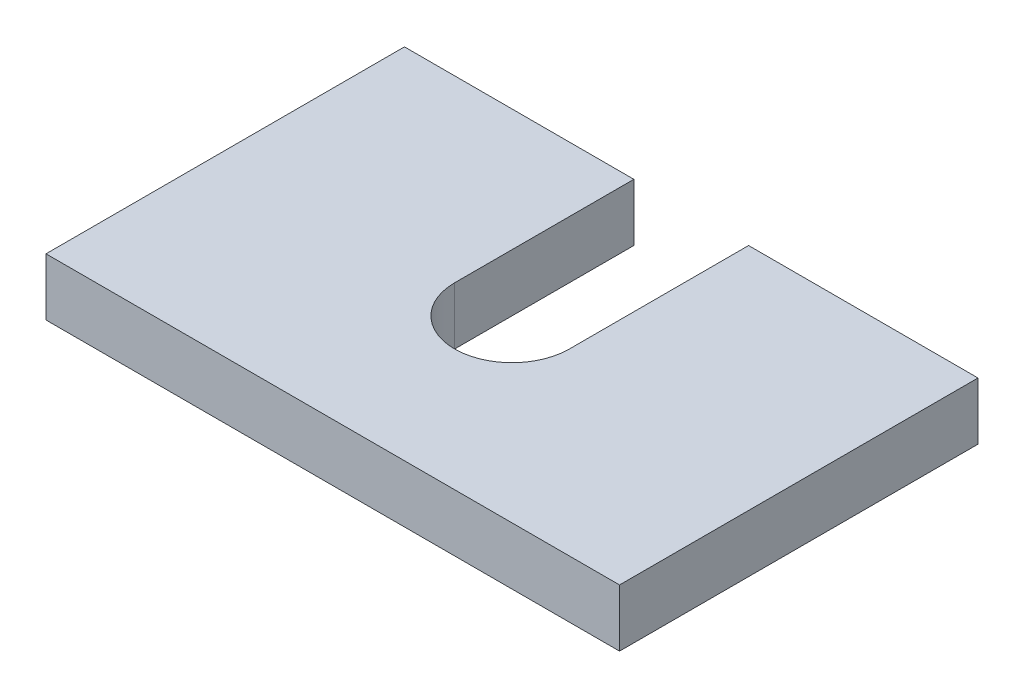
SolidWorks part; units mm, degrees
material "AISI 4340 Steel, normalized"
ref_plane "Front Plane" through (0, 0, 0) normal (0, 0, 1) x (1, 0, 0)
ref_plane "Top Plane" through (0, 0, 0) normal (0, 1, 0) x (1, 0, 0)
ref_plane "Right Plane" through (0, 0, 0) normal (1, 0, 0) x (0, 0, -1)
sketch "Sketch1" plane through (0, 0, 0) normal (0, 1, 0) x (1, 0, 0)
  line L0 (-4, 0) -> (-4, 12.5)
  line L1 (-20, -12.5) -> (20, -12.5)
  line L2 (-20, -12.5) -> (-20, 12.5)
  line L3 (-20, 12.5) -> (-4, 12.5)
  line L4 (20, -12.5) -> (20, 12.5)
  line L5 (0, 12.5) -> (0, -12.5) construction
  line L6 (-20, 0) -> (20, 0) construction
  line L7 (4, 0) -> (4, 12.5)
  line L8 (4, 12.5) -> (20, 12.5)
  line L9 (-4, 12.5) -> (4, 12.5) construction
  arc A0 (-4, 0) -> (4, 0) centre (0, 0) ccw
  point P0 (0, 0)
  dimension "D3" = 8
  dimension "D1" = 40
  dimension "D2" = 25
extrude "Boss-Extrude1" add sketch "Sketch1" along normal blind 4
